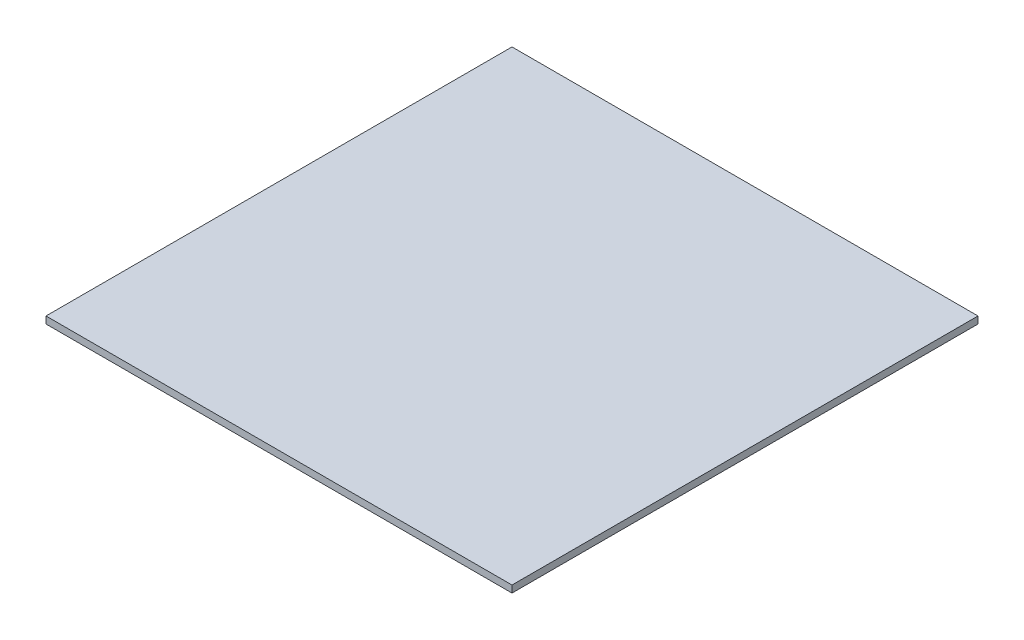
SolidWorks part; units mm, degrees
ref_plane "Front Plane" through (0, 0, 0) normal (0, 0, 1) x (1, 0, 0)
ref_plane "Top Plane" through (0, 0, 0) normal (0, 1, 0) x (1, 0, 0)
ref_plane "Right Plane" through (0, 0, 0) normal (1, 0, 0) x (0, 0, -1)
sketch "Sketch1" plane through (0, 0, 0) normal (0, 1, 0) x (1, 0, 0)
  line L1 (-100, -100) -> (100, -100)
  line L2 (-100, -100) -> (-100, 100)
  line L3 (-100, 100) -> (100, 100)
  line L4 (100, -100) -> (100, 100)
  line L5 (-100, -100) -> (100, 100) construction
  line L6 (-100, 100) -> (100, -100) construction
  point P0 (0, 0)
  dimension "D1" = 200
  dimension "D2" = 200
extrude "Boss-Extrude1" add sketch "Sketch1" along normal blind 3
split line "Split Line4" [suppressed]
